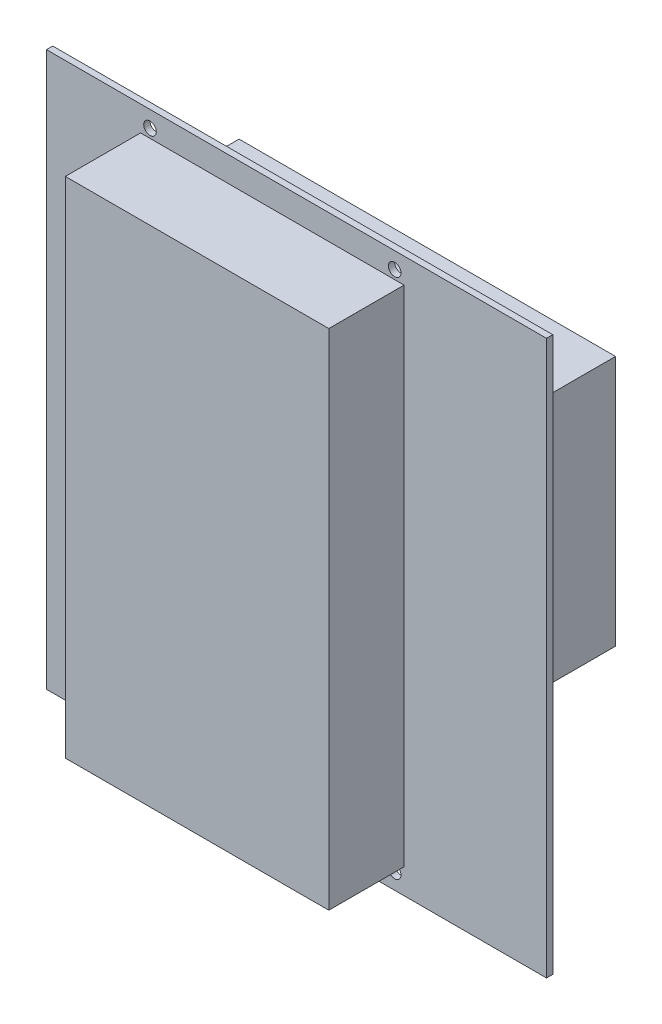
SolidWorks part; units mm, degrees
ref_plane "Front Plane" through (0, 0, 0) normal (0, 0, 1) x (1, 0, 0)
ref_plane "Top Plane" through (0, 0, 0) normal (0, 1, 0) x (1, 0, 0)
ref_plane "Right Plane" through (0, 0, 0) normal (1, 0, 0) x (0, 0, -1)
sketch "Sketch1" plane through (0, 0, 0) normal (0, 0, 1) x (1, 0, 0)
  line L0 (0, 121.439) -> (0, -129.4022) construction
  line L1 (-57.9545, 0) -> (61.9361, 0) construction
  line L2 (-50.6095, 56.0705) -> (50.6095, 56.0705)
  line L3 (50.6095, 56.0705) -> (50.6095, -56.0705)
  line L4 (50.6095, -56.0705) -> (-50.6095, -56.0705)
  line L5 (-50.6095, -56.0705) -> (-50.6095, 56.0705)
  point P7 (0, 56.0705)
  point P10 (-50.6095, 0)
  dimension "D1" = 101.219
  dimension "D2" = 112.141
extrude "Boss-Extrude1" add sketch "Sketch1" along normal blind 1.27 contours L2 L3 L4 L5
sketch "Sketch2" plane through (0, 0, 1.27) normal (0, 0, 1) x (1, 0, 0)
  line L0 (-31.5595, 50.9905) -> (21.7805, 50.9905)
  line L2 (21.7805, 50.9905) -> (21.7805, -50.9905)
  line L4 (21.7805, -50.9905) -> (-31.5595, -50.9905)
  line L5 (-31.5595, -50.9905) -> (-31.5595, 50.9905)
  line L6 (-4.8895, 54.5824) -> (-4.8895, -54.7823) construction
  line L8 (-50.6095, -56.0705) -> (-50.6095, 56.0705) construction
  line L9 (-50.6095, 56.0705) -> (50.6095, 56.0705) construction
  line L10 (50.6095, -56.0705) -> (-50.6095, -56.0705) construction
  point P4 (-4.8895, 50.9905)
  point P9 (-4.8895, -50.9905)
  dimension "D1" = 53.34
  dimension "D2" = 19.05
  dimension "D3" = 5.08
  dimension "D4" = 5.08
extrude "Boss-Extrude2" add sketch "Sketch2" along normal blind 15.24
sketch "Sketch3" plane through (0, 0, 0) normal (0, 0, -1) x (-1, 0, 0)
  line L0 (50.6095, 56.0705) -> (-50.6095, 56.0705) construction
  line L1 (-41.7195, 37.0205) -> (34.4805, 37.0205)
  line L2 (-41.7195, 37.0205) -> (-41.7195, -13.7795)
  line L3 (-41.7195, -13.7795) -> (34.4805, -13.7795)
  line L4 (34.4805, 37.0205) -> (34.4805, -13.7795)
  line L5 (-50.6095, 56.0705) -> (-50.6095, -56.0705) construction
  dimension "D1" = 76.2
  dimension "D2" = 50.8
  dimension "D3" = 19.05
  dimension "D4" = 8.89
extrude "Boss-Extrude3" add sketch "Sketch3" along normal blind 21.59
sketch "Sketch4" plane through (0, 0, 1.27) normal (0, 0, 1) x (1, 0, 0)
  line L0 (-50.6095, 56.0705) -> (50.6095, 56.0705) construction
  line L1 (-50.6095, -56.0705) -> (-50.6095, 56.0705) construction
  circle A0 centre (-29.6545, 52.7685) radius 1.27
  circle A1 centre (19.8755, 52.7685) radius 1.27
  circle A2 centre (-29.6545, -52.7685) radius 1.27
  circle A3 centre (19.8755, -52.7685) radius 1.27
  dimension "D5" = 2.54
  dimension "D6" = 2.54
  dimension "D7" = 2.54
  dimension "D8" = 2.54
  dimension "D1" = 3.302
  dimension "D2" = 108.839
  dimension "D3" = 20.955
  dimension "D4" = 70.485
extrude "Cut-Extrude1" cut sketch "Sketch4" against normal through all and the other way through all
equation "\"D6@Sketch4\"=\"D5@Sketch4\""
equation "\"D7@Sketch4\"=\"D5@Sketch4\""
equation "\"D8@Sketch4\"=\"D5@Sketch4\""
